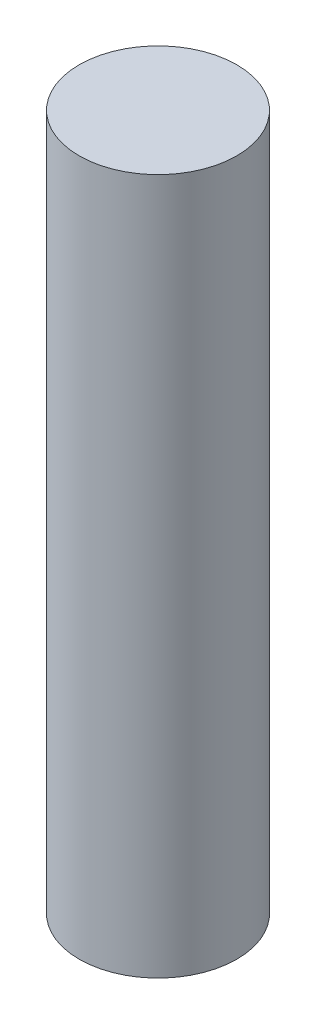
SolidWorks part; units mm, degrees
ref_plane "Front Plane" through (0, 0, 0) normal (0, 0, 1) x (1, 0, 0)
ref_plane "Top Plane" through (0, 0, 0) normal (0, 1, 0) x (1, 0, 0)
ref_plane "Right Plane" through (0, 0, 0) normal (1, 0, 0) x (0, 0, -1)
sketch "Sketch1" plane through (0, 0, 0) normal (0, 1, 0) x (1, 0, 0)
  circle A0 centre (0, 0) radius 3.4
  dimension "D1" = 6.8
extrude "Boss-Extrude1" add sketch "Sketch1" along normal blind 30
